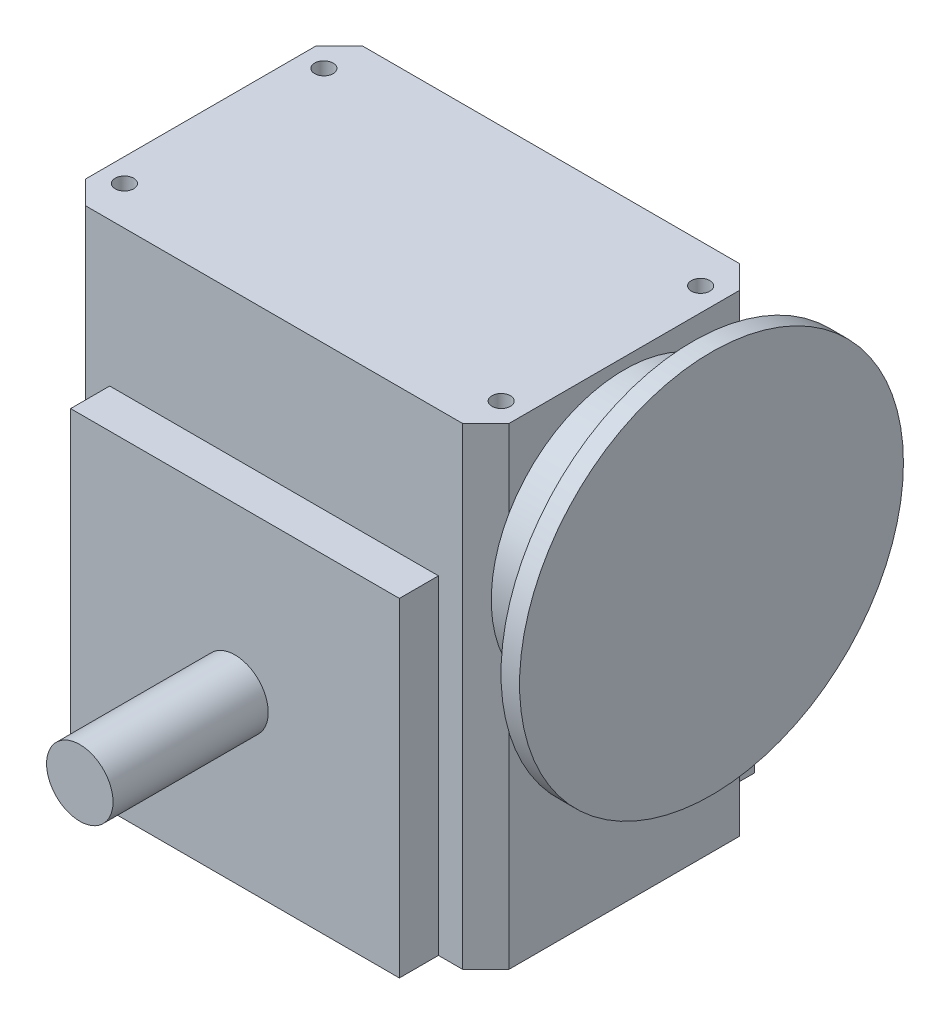
SolidWorks part; units mm, degrees
ref_plane "Front" through (0, 0, 0) normal (0, 0, 1) x (1, 0, 0)
ref_plane "Top" through (0, 0, 0) normal (0, 1, 0) x (1, 0, 0)
ref_plane "Right" through (0, 0, 0) normal (1, 0, 0) x (0, 0, -1)
sketch "Sketch1" plane through (0, 0, 0) normal (0, 1, 0) x (1, 0, 0)
  line L1 (-90.9955, 59.4995) -> (90.9955, 59.4995)
  line L2 (-90.9955, 59.4995) -> (-90.9955, -59.4995)
  line L3 (-90.9955, -59.4995) -> (90.9955, -59.4995)
  line L4 (90.9955, 59.4995) -> (90.9955, -59.4995)
  line L5 (-90.9955, 59.4995) -> (90.9955, -59.4995) construction
  line L6 (-90.9955, -59.4995) -> (90.9955, 59.4995) construction
  point P0 (0, 0)
  dimension "D1" = 181.991
  dimension "D2" = 118.999
extrude "Boss-Extrude1" add sketch "Sketch1" along normal blind 203.2
sketch "Sketch2" plane through (0, 0, 59.4995) normal (0, 0, 1) x (1, 0, 0)
  line L0 (-90.9955, 0) -> (90.9955, 0) construction
  line L1 (-70.6501, 0) -> (70.6501, 0)
  line L2 (-70.6501, 0) -> (-70.6501, 141.3002)
  line L3 (-70.6501, 141.3002) -> (70.6501, 141.3002)
  line L4 (70.6501, 0) -> (70.6501, 141.3002)
  line L5 (70.6501, 74.6252) -> (0, 74.6252) construction
  line L6 (0, 74.6252) -> (-70.6501, 74.6252) construction
  line L7 (0, 74.6252) -> (0, 0) construction
  point P4 (0, 74.6252)
  dimension "D1" = 74.6252
  dimension "D2" = 66.675
  dimension "D3" = 141.3002
extrude "Boss-Extrude2" add sketch "Sketch2" along normal blind 16.8021
sketch "Sketch3" plane through (0, 0, 76.3016) normal (0, 0, 1) x (1, 0, 0)
  line L0 (70.6501, 141.3002) -> (-70.6501, 0) construction
  line L1 (-70.6501, 141.3002) -> (70.6501, 0) construction
  circle A0 centre (0, 70.6501) radius 14.2875
  dimension "D1" = 28.575
extrude "Boss-Extrude3" add sketch "Sketch3" along normal blind 66.7004
sketch "Sketch4" plane through (0, 0, 0) normal (0, -1, 0) x (1, 0, 0)
  line L0 (-80.9625, 0) -> (-90.9955, 0) construction
  line L1 (-80.9625, -42.8625) -> (80.9625, -42.8625) construction
  line L2 (-80.9625, -42.8625) -> (-80.9625, 42.8625) construction
  line L3 (-80.9625, 42.8625) -> (80.9625, 42.8625) construction
  line L4 (80.9625, -42.8625) -> (80.9625, 42.8625) construction
  line L5 (-80.9625, -42.8625) -> (80.9625, 42.8625) construction
  line L6 (-80.9625, 42.8625) -> (80.9625, -42.8625) construction
  line L7 (-90.9955, -59.4995) -> (-90.9955, 59.4995) construction
  line L8 (80.9625, 0) -> (90.9955, 0) construction
  line L9 (90.9955, 59.4995) -> (90.9955, -59.4995) construction
  line L10 (-70.6501, 59.4995) -> (70.6501, 59.4995) construction
  line L11 (0, 42.8625) -> (0, 59.4995) construction
  line L12 (0, -42.8625) -> (0, -59.4995) construction
  line L13 (90.9955, -59.4995) -> (-90.9955, -59.4995) construction
  circle A0 centre (-80.9625, -42.8625) radius 4.6642
  circle A1 centre (-80.9625, 42.8625) radius 3.9201
  circle A2 centre (80.9625, 42.8625) radius 3.9674
  circle A3 centre (80.9625, -42.8625) radius 5.7174
  point P4 (0, 0)
  dimension "D1" = 161.925
  dimension "D2" = 85.725
sketch "Sketch6" plane through (0, 203.2, 0) normal (0, 1, 0) x (1, 0, 0)
  circle A1 centre (80.9625, 42.8625) radius 5.7174
  circle A2 centre (80.9625, 42.8625) radius 5.7174
  circle A3 centre (80.9625, -42.8625) radius 3.9674
  circle A4 centre (80.9625, -42.8625) radius 3.9674
  circle A5 centre (-80.9625, -42.8625) radius 3.9201
  circle A6 centre (-80.9625, -42.8625) radius 3.9201
  circle A7 centre (-80.9625, 42.8625) radius 4.6642
  circle A8 centre (-80.9625, 42.8625) radius 4.6642
  dimension "D1" = 0
  dimension "D2" = 0
  dimension "D3" = 0
  dimension "D4" = 0
hole_wizard "Tap Drill for 3/8-16 Tap1" positions "3DSketch1" profile "Sketch5" hole size "3/8-16" standard "ANSI Inch"
sketch3d "3DSketch1"
  point P0 (-80.9625, 0, -42.8625)
  point P3 (-80.9625, 0, 42.8625)
  point P6 (80.9625, 0, 42.8625)
  point P9 (80.9625, 0, -42.8625)
  point P13 (80.9625, 203.2, -42.8625)
  point P16 (80.9625, 203.2, 42.8625)
  point P19 (-80.9625, 203.2, 42.8625)
  point P22 (-80.9625, 203.2, -42.8625)
sketch "Sketch5" plane through (-80.9625, 0, -42.8625) normal (1, 0, 0) x (0, 0, -1)
  line L0 (0, 0) -> (0, 15.0847)
  line L1 (0, 15.0847) -> (3.9687, 12.7)
  line L2 (3.9687, 12.7) -> (3.9687, 0)
  line L5 (3.9687, 0) -> (0, 0)
  line L10 (0, 15.0847) -> (-3.9688, 12.7) construction
  line L11 (0, -6.35) -> (0, 107.95) construction
  dimension "Hole Dia." = 7.9375
  dimension "Hole Depth" = 12.7
  dimension "Drill Angle" = 118
chamfer "Chamfer1" distance 10.033 angle 45 4 edges at (-90.9955, 101.6, -59.4995) (-90.9955, 101.6, 59.4995) (90.9955, 101.6, -59.4995) (90.9955, 101.6, 59.4995)
mirror "Mirror1" about plane through (0, 0, 0) normal (0, 0, 1) of "Boss-Extrude2"
sketch "Sketch7" plane through (90.9955, 0, 0) normal (1, 0, 0) x (0, 0, -1)
  line L0 (0, 141.3002) -> (0, 0) construction
  circle A0 centre (0, 141.3002) radius 57.15
  dimension "D2" = 114.3
  dimension "D1" = 141.3002
extrude "Boss-Extrude4" add sketch "Sketch7" along normal blind 37.5031
sketch "Sketch8" plane through (128.4986, 0, 0) normal (1, 0, 0) x (0, 0, -1)
  circle A0 centre (0, 141.3002) radius 82.4992
  dimension "D1" = 164.9984
extrude "Boss-Extrude5" add sketch "Sketch8" against normal blind 7.9756
